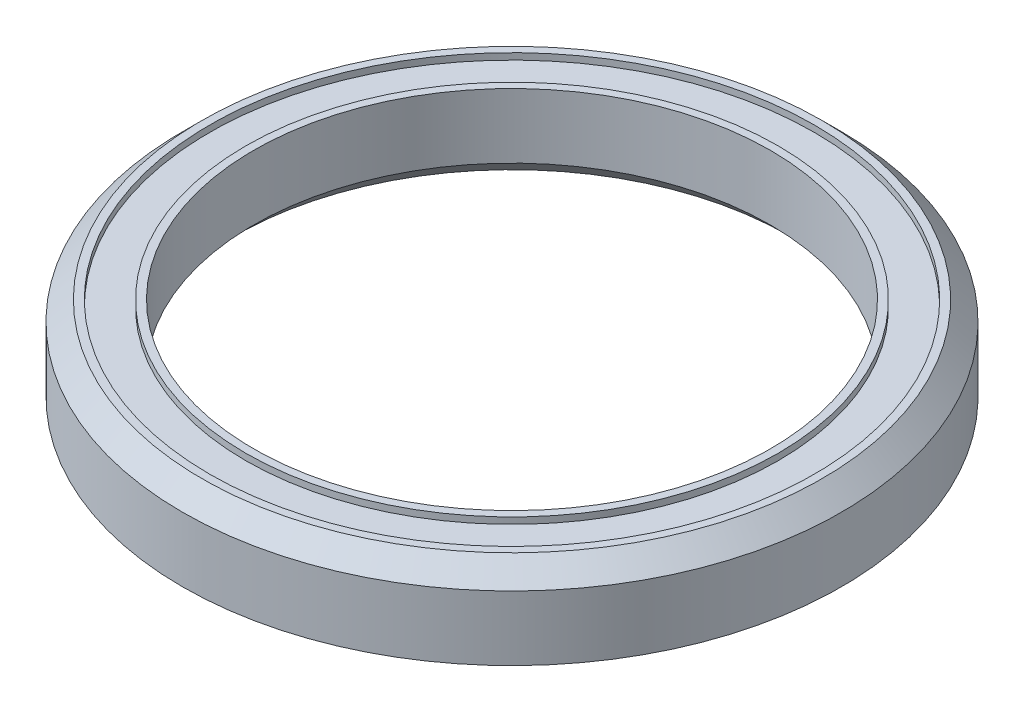
SolidWorks part; units mm, degrees
ref_plane "前视基准面" through (0, 0, 0) normal (0, 0, 1) x (1, 0, 0)
ref_plane "上视基准面" through (0, 0, 0) normal (0, 1, 0) x (1, 0, 0)
ref_plane "右视基准面" through (0, 0, 0) normal (1, 0, 0) x (0, 0, -1)
sketch "草图1" plane through (0, 0, 0) normal (0, 1, 0) x (1, 0, 0)
  circle A0 centre (0, 0) radius 20
  circle A1 centre (0, 0) radius 25.5
  dimension "D1" = 40
  dimension "D2" = 51
extrude "凸台-拉伸1" add sketch "草图1" along normal blind 6.5
chamfer "倒角1" distance 1.5 angle 45 1 edges at (0, 6.5, 25.5)
chamfer "倒角2" distance 1.5 angle 45 1 edges at (0, 0, 20)
sketch "草图2" plane through (0, 6.5, 0) normal (0, 1, 0) x (1, 0, 0)
  circle A0 centre (0, 0) radius 20.6
  circle A1 centre (0, 0) radius 23.4
  circle A2 centre (0, 0) radius 24 construction
  circle A3 centre (0, 0) radius 20 construction
  dimension "D1" = 0.6
  dimension "D2" = 0.6
extrude "切除-拉伸1" cut sketch "草图2" against normal blind 0.5
sketch "草图3" plane through (0, 0, 0) normal (0, -1, 0) x (1, 0, 0)
  circle A0 centre (0, 0) radius 22.1
  circle A1 centre (0, 0) radius 24.9
  circle A2 centre (0, 0) radius 21.5 construction
  circle A3 centre (0, 0) radius 25.5 construction
  dimension "D1" = 0.6
  dimension "D2" = 0.6
extrude "切除-拉伸2" cut sketch "草图3" against normal blind 0.5
